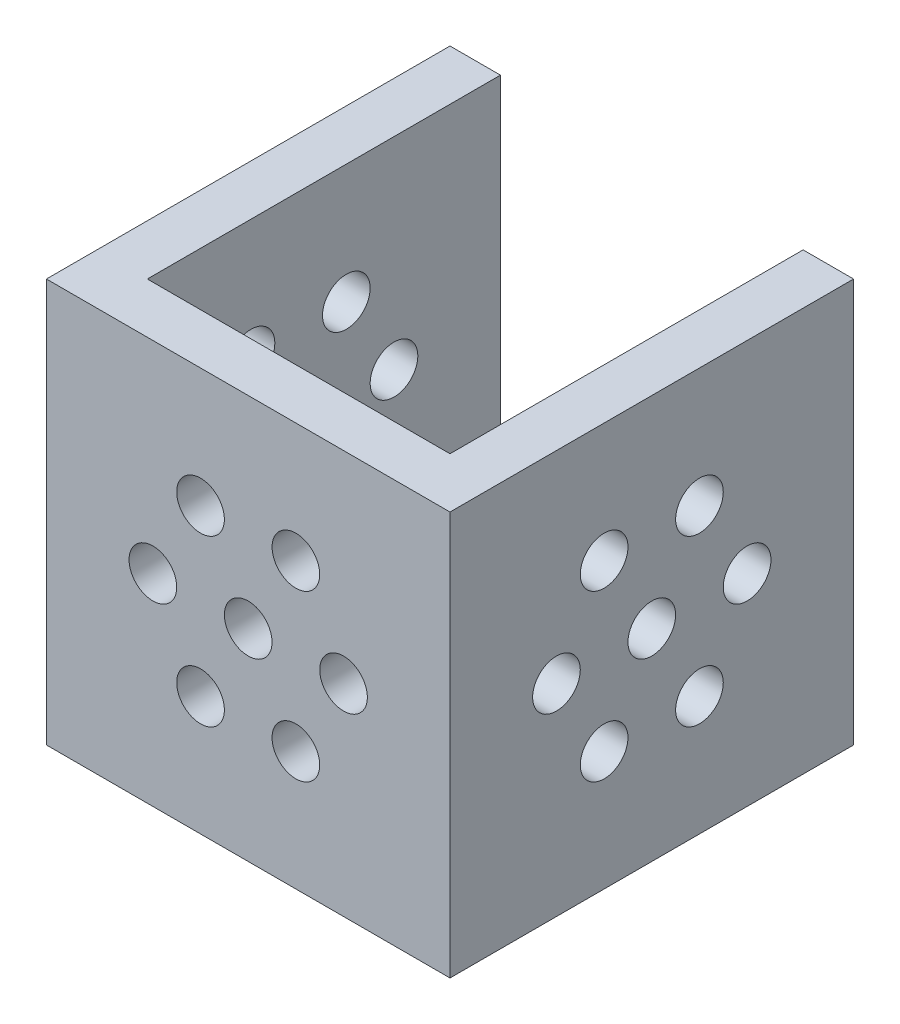
SolidWorks part; units mm, degrees
ref_plane "Front" through (0, 0, 0) normal (0, 0, 1) x (1, 0, 0)
ref_plane "Top" through (0, 0, 0) normal (0, 1, 0) x (1, 0, 0)
ref_plane "Right" through (0, 0, 0) normal (1, 0, 0) x (0, 0, -1)
sketch "Sketch2" plane through (0, 0, 0) normal (0, 1, 0) x (1, 0, 0)
  line L0 (12.7, 25.4) -> (12.7, 3.175)
  line L1 (0, 0) -> (25.4, 0)
  line L2 (0, 0) -> (0, 25.4)
  line L3 (0, 25.4) -> (25.4, 25.4)
  line L4 (25.4, 0) -> (25.4, 25.4)
  line L5 (12.7, 3.175) -> (22.225, 3.175)
  line L6 (12.7, 3.175) -> (3.175, 3.175)
  line L7 (3.175, 3.175) -> (3.175, 25.4)
  line L8 (22.225, 3.175) -> (22.225, 25.4)
  dimension "D1" = 25.4
  dimension "D2" = 25.4
  dimension "D3" = 22.225
  dimension "D4" = 9.525
  dimension "D5" = 9.525
extrude "Boss-Extrude1" add sketch "Sketch2" along normal blind 25.4 contours L8 L5 L6 L7 L3 L2 L1 L4
sketch "Sketch3" plane through (0, 0, 0) normal (0, 0, 1) x (1, 0, 0)
  line L0 (12.7, 0) -> (12.7, 25.4)
  line L1 (0, 0) -> (25.4, 0) construction
  line L2 (0, 25.4) -> (25.4, 25.4) construction
  line L3 (12.7, 12.7) -> (6.7, 12.7)
  circle A0 centre (12.7, 12.7) radius 1.5
  circle A1 centre (6.7, 12.7) radius 1.5
  circle A2 centre (9.7, 17.8962) radius 1.5
  circle A3 centre (15.7, 17.8962) radius 1.5
  circle A4 centre (18.7, 12.7) radius 1.5
  circle A5 centre (15.7, 7.5038) radius 1.5
  circle A6 centre (9.7, 7.5038) radius 1.5
  point P10 (0, 0)
  point P27 (12.7, 12.7)
  dimension "D1" = 6
  dimension "D2" = 6
extrude "Cut-Extrude1" cut sketch "Sketch3" against normal through all
sketch "Sketch4" plane through (25.4, 0, 0) normal (1, 0, 0) x (0, 0, -1)
  line L0 (12.7, 0) -> (12.7, 25.4)
  line L1 (0, 0) -> (25.4, 0) construction
  line L2 (0, 25.4) -> (25.4, 25.4) construction
  line L3 (12.7, 12.7) -> (6.7, 12.7)
  circle A0 centre (12.7, 12.7) radius 1.5
  circle A1 centre (6.7, 12.7) radius 1.5
  circle A2 centre (9.7, 17.8962) radius 1.5
  circle A3 centre (15.7, 17.8962) radius 1.5
  circle A4 centre (18.7, 12.7) radius 1.5
  circle A5 centre (15.7, 7.5038) radius 1.5
  circle A6 centre (9.7, 7.5038) radius 1.5
  point P23 (12.7, 12.7)
  dimension "D1" = 6
  dimension "D2" = 6
extrude "Cut-Extrude2" cut sketch "Sketch4" against normal through all
